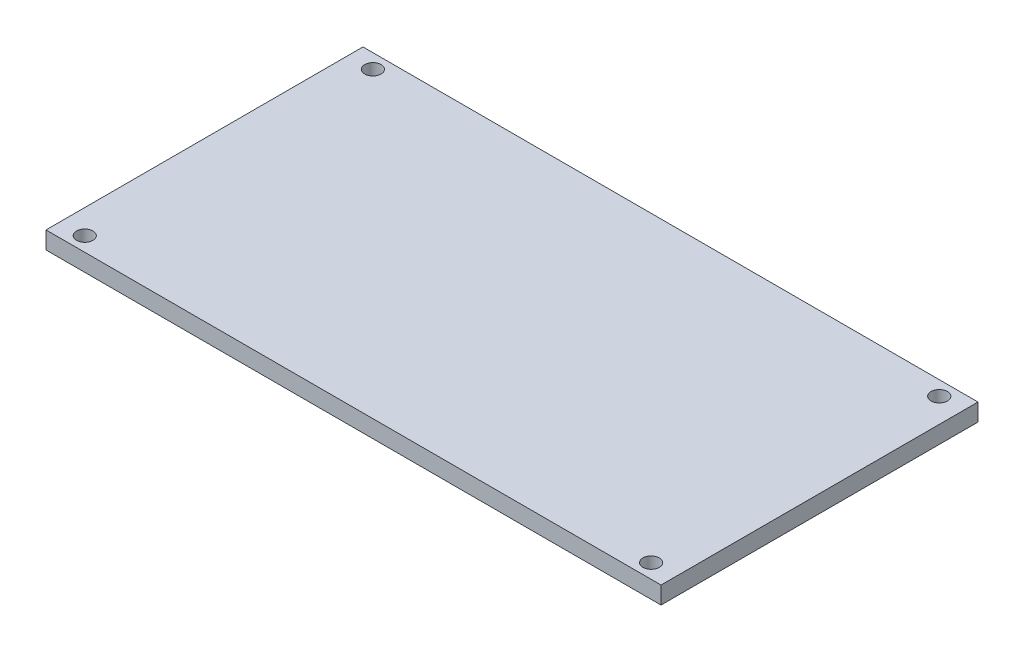
SolidWorks part; units mm, degrees
ref_plane "Ebene vorne" through (0, 0, 0) normal (0, 0, 1) x (1, 0, 0)
ref_plane "Ebene oben" through (0, 0, 0) normal (0, 1, 0) x (1, 0, 0)
ref_plane "Ebene rechts" through (0, 0, 0) normal (1, 0, 0) x (0, 0, -1)
sketch "Sketch1" plane through (0, 0, 0) normal (0, 1, 0) x (1, 0, 0)
  line L1 (-61.9, -31.9) -> (61.9, -31.9)
  line L2 (-61.9, -31.9) -> (-61.9, 31.9)
  line L3 (-61.9, 31.9) -> (61.9, 31.9)
  line L4 (61.9, -31.9) -> (61.9, 31.9)
  line L5 (-61.9, -31.9) -> (61.9, 31.9) construction
  line L6 (-61.9, 31.9) -> (61.9, -31.9) construction
  circle A0 centre (-57, 29) radius 1.65
  circle A1 centre (57, 29) radius 1.65
  circle A2 centre (57, -29) radius 1.65
  circle A3 centre (-57, -29) radius 1.65
  point P0 (0, 0)
  dimension "D3" = 3.3
  dimension "D4" = 3.3
  dimension "D5" = 3.3
  dimension "D6" = 3.3
  dimension "D1" = 63.8
  dimension "D2" = 123.8
  dimension "D7" = 4.9
  dimension "D8" = 2.9
  dimension "D9" = 2.9
  dimension "D10" = 4.9
  dimension "D11" = 2.9
  dimension "D12" = 4.9
  dimension "D13" = 2.9
  dimension "D14" = 4.9
extrude "Extrude1" add sketch "Sketch1" along normal blind 3.5 contours L1 L4 L3 L2 A3 A2 A1 A0
